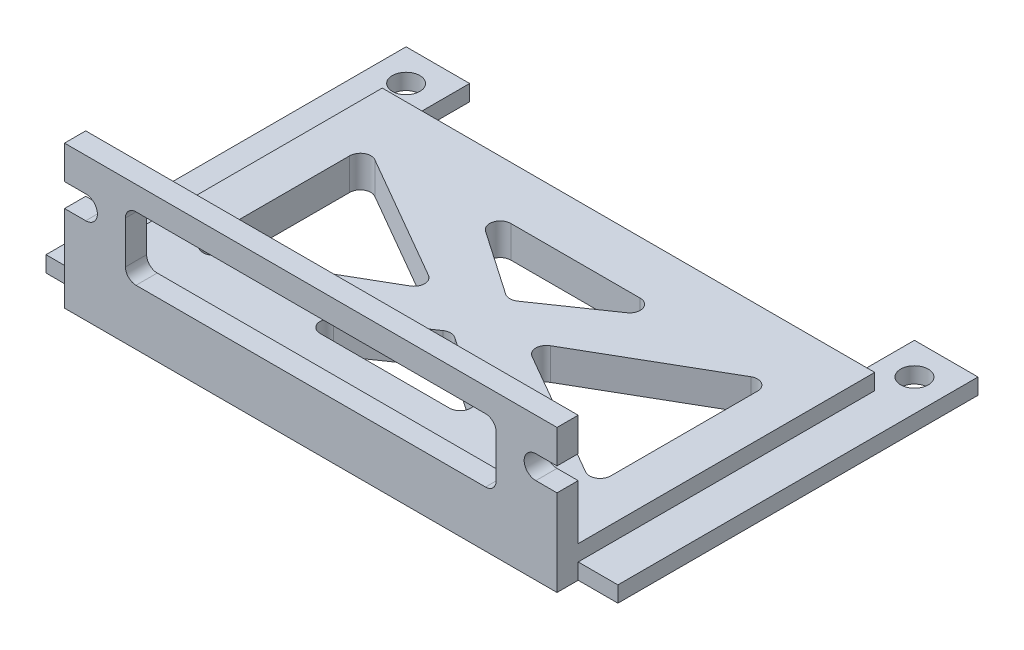
SolidWorks part; units mm, degrees
ref_plane "前视基准面" through (0, 0, 0) normal (0, 0, 1) x (1, 0, 0)
ref_plane "上视基准面" through (0, 0, 0) normal (0, 1, 0) x (1, 0, 0)
ref_plane "右视基准面" through (0, 0, 0) normal (1, 0, 0) x (0, 0, -1)
sketch "草图1" plane through (0, 0, 0) normal (0, 1, 0) x (1, 0, 0)
  line L1 (-46.5, -28) -> (46.5, -28) construction
  line L2 (-46.5, -28) -> (-46.5, 28) construction
  line L3 (-46.5, 28) -> (46.5, 28) construction
  line L4 (46.5, -28) -> (46.5, 28) construction
  line L5 (-46.5, -28) -> (46.5, 28) construction
  line L6 (-46.5, 28) -> (46.5, -28) construction
  line L7 (-58, -28) -> (58, -28)
  line L8 (-58, -28) -> (-58, 28)
  line L9 (-58, 28) -> (58, 28)
  line L10 (58, -28) -> (58, 28)
  line L11 (-58, -28) -> (58, 28) construction
  line L12 (-58, 28) -> (58, -28) construction
  point P0 (0, 0)
  point P6 (0, 0)
  dimension "D1" = 56
  dimension "D2" = 93
  dimension "D3" = 56
  dimension "D4" = 116
extrude "凸台-拉伸1" add sketch "草图1" along normal blind 3
sketch "草图2" plane through (0, 3, 0) normal (0, 1, 0) x (1, 0, 0)
  line L1 (-46.5, -28) -> (46.5, -28)
  line L2 (-46.5, -28) -> (-46.5, 28)
  line L3 (-46.5, 28) -> (46.5, 28)
  line L4 (46.5, -28) -> (46.5, 28)
  line L5 (-46.5, -28) -> (46.5, 28) construction
  line L6 (-46.5, 28) -> (46.5, -28) construction
  point P0 (0, 0)
extrude "凸台-拉伸2" add sketch "草图2" along normal blind 3
sketch "草图3" plane through (0, 0, 28) normal (0, 0, 1) x (1, 0, 0)
  line L0 (-46.5, 0) -> (-46.5, 27)
  line L1 (-58, 0) -> (58, 0) construction
  line L2 (-58, 0) -> (58, 0) construction
  line L3 (-46.5, 27) -> (46.5, 27)
  line L4 (46.5, 27) -> (46.5, 0)
  line L5 (-46.5, 0) -> (46.5, 0) construction
  line L6 (46.5, 0) -> (-46.5, 0)
  dimension "D1" = 27
  dimension "D2" = 93
extrude "凸台-拉伸3" add sketch "草图3" along normal blind 4
sketch "草图4" plane through (0, 3, 0) normal (0, 1, 0) x (1, 0, 0)
  line L0 (-46.5, 28) -> (-58, 28) construction
  line L1 (48, -34) -> (-48, -34) construction
  line L2 (48, -34) -> (48, 34) construction
  line L3 (48, 34) -> (-48, 34) construction
  line L4 (-48, -34) -> (-48, 34) construction
  line L5 (48, -34) -> (-48, 34) construction
  line L6 (48, 34) -> (-48, -34) construction
  point P0 (0, 0)
  point P6 (-48, 32.3311)
  dimension "D1" = 96
  dimension "D2" = 6
sketch "草图5" plane through (0, 3, 0) normal (0, 1, 0) x (1, 0, 0)
  line L5 (54, 40) -> (42, 40)
  line L6 (-54, 28) -> (-42, 28)
  line L7 (0, -12.7262) -> (0, 42.4626) construction
  line L12 (-54, 28) -> (-54, 40)
  line L13 (-54, 40) -> (-42, 40)
  line L14 (-42, 28) -> (-42, 40)
  line L15 (-54, 28) -> (-42, 40) construction
  line L16 (-54, 40) -> (-42, 28) construction
  line L17 (42, 28) -> (42, 40)
  line L18 (54, 28) -> (42, 28)
  line L19 (54, 28) -> (54, 40)
  point P0 (-48, 34)
  point P1 (-48, 34)
  dimension "D1" = 12
  dimension "D2" = 12
extrude "凸台-拉伸4" add sketch "草图5" against normal blind 3
sketch "草图6" plane through (0, 3, 0) normal (0, 1, 0) x (1, 0, 0)
  circle A0 centre (-48, 34) radius 2.6
  circle A1 centre (48, 34) radius 2.6
  dimension "D1" = 5.2
  dimension "D2" = 5.2
extrude "切除-拉伸1" cut sketch "草图6" against normal blind 3
sketch "草图7" plane through (0, 6, 0) normal (0, 1, 0) x (1, 0, 0)
  line L0 (-3.6525, 7.6752) -> (-32.1835, 27.3217) construction
  line L5 (48, 34) -> (-48, -34) construction
  line L6 (28.5, -18) -> (-28.5, -18) construction
  line L7 (-18.6463, 18) -> (0, 5.1602)
  line L8 (28.5, -18) -> (28.5, 18) construction
  line L9 (28.5, 18) -> (-28.5, 18) construction
  line L10 (-28.5, -18) -> (-28.5, 18) construction
  line L11 (28.5, -18) -> (-28.5, 18) construction
  line L12 (28.5, 18) -> (-28.5, -18) construction
  line L13 (-46.5, 28) -> (-46.5, -28) construction
  line L14 (46.5, 28) -> (-46.5, 28) construction
  line L15 (-4.426, 0) -> (4.9863, 0) construction
  line L16 (-8.5, 0) -> (-38.5, 17.3205)
  line L17 (-38.5, 17.3205) -> (-38.5, -17.3205)
  line L18 (-38.5, -17.3205) -> (-8.5, 0)
  line L19 (0, 6.0975) -> (0, -6.8288) construction
  line L20 (-18.6463, 18) -> (18.6463, 18)
  line L21 (18.6463, 18) -> (0, 5.1602)
  line L22 (38.5, -17.3205) -> (8.5, 0)
  line L23 (38.5, 17.3205) -> (38.5, -17.3205)
  line L24 (8.5, 0) -> (38.5, 17.3205)
  line L25 (-18.6463, -18) -> (18.6463, -18)
  line L26 (-18.6463, -18) -> (0, -5.1602)
  line L27 (18.6463, -18) -> (0, -5.1602)
  circle A0 centre (-28.5, 0) radius 10 construction
  point P0 (0, 0)
  point P27 (0, 18)
  dimension "D1" = 18
  dimension "D2" = 10
  dimension "D3" = 20
extrude "切除-拉伸2" cut sketch "草图7" against normal through all
sketch "草图8" plane through (0, 0, 28) normal (0, 0, -1) x (-1, 0, 0)
  line L0 (-46.5, 16.5) -> (0, 16.5) construction
  line L1 (-46.5, 6) -> (-46.5, 27) construction
  line L2 (0, 27) -> (0, 6) construction
  line L3 (-46.5, 27) -> (46.5, 27) construction
  line L4 (-46.5, 6) -> (46.5, 6) construction
  line L6 (-35, 10.5) -> (35, 10.5)
  line L7 (-35, 10.5) -> (-35, 22.5)
  line L8 (-35, 22.5) -> (35, 22.5)
  line L9 (35, 10.5) -> (35, 22.5)
  line L10 (-35, 10.5) -> (35, 22.5) construction
  line L11 (-35, 22.5) -> (35, 10.5) construction
  dimension "D1" = 70
  dimension "D2" = 12
extrude "切除-拉伸3" cut sketch "草图8" against normal through all
sketch "草图9" plane through (0, 0, -28) normal (0, 0, -1) x (-1, 0, 0)
  line L4 (54, 3) -> (54, 0)
  line L5 (54, 0) -> (58, 0)
  line L6 (58, 0) -> (58, 3)
  line L7 (58, 3) -> (54, 3)
  line L8 (54, 3) -> (54, 0)
  line L9 (54, 0) -> (58, 0)
  line L10 (58, 0) -> (58, 3)
  line L11 (58, 3) -> (54, 3)
  line L12 (-58, 0) -> (-54, 0)
  line L13 (-54, 0) -> (-54, 3)
  line L14 (-54, 3) -> (-58, 3)
  line L15 (-58, 3) -> (-58, 0)
  line L16 (-58, 0) -> (-54, 0)
  line L17 (-54, 0) -> (-54, 3)
  line L18 (-54, 3) -> (-58, 3)
  line L19 (-58, 3) -> (-58, 0)
  dimension "D1" = 0
  dimension "D2" = 0
extrude "切除-拉伸4" cut sketch "草图9" against normal through all
sketch "草图10" plane through (0, 0, 28) normal (0, 0, -1) x (-1, 0, 0)
  line L0 (-46.5, 18.5) -> (46.5, 18.5) construction
  line L1 (-46.5, 6) -> (-46.5, 27) construction
  line L2 (46.5, 27) -> (46.5, 6) construction
  line L3 (46.5, 6) -> (-46.5, 6) construction
  line L4 (-46.5, 18.5) -> (-42.5, 18.5) construction
  line L5 (-46.5, 20.7) -> (-42.5, 20.7)
  line L6 (-46.5, 16.3) -> (-42.5, 16.3)
  line L7 (0, 6) -> (0, 27) construction
  line L8 (-46.5, 27) -> (46.5, 27) construction
  line L9 (46.5, 18.5) -> (42.5, 18.5) construction
  line L10 (46.5, 20.7) -> (42.5, 20.7)
  line L11 (46.5, 16.3) -> (42.5, 16.3)
  arc A0 (-46.5, 20.7) -> (-46.5, 16.3) centre (-46.5, 18.5) ccw
  arc A1 (-42.5, 16.3) -> (-42.5, 20.7) centre (-42.5, 18.5) ccw
  arc A2 (46.5, 20.7) -> (46.5, 16.3) centre (46.5, 18.5) cw
  arc A3 (42.5, 16.3) -> (42.5, 20.7) centre (42.5, 18.5) cw
  point P8 (-44.5, 18.5)
  point P19 (44.5, 18.5)
  dimension "D3" = 2.2
  dimension "D1" = 12.5
  dimension "D2" = 4
extrude "切除-拉伸5" cut sketch "草图10" against normal through all
fillet "圆角1" radius 2 16 edges at (35, 22.5, 30) (-35, 22.5, 30) (-35, 10.5, 30) (35, 10.5, 30) (-38.5, 3, -17.3205) (-18.6463, 3, -18) (-38.5, 3, 17.3205) (0, 3, -5.1602) (18.6463, 3, -18) (-8.5, 3, 0) (-18.6463, 3, 18) (0, 3, 5.1602) (18.6463, 3, 18) (8.5, 3, 0) (38.5, 3, -17.3205) (38.5, 3, 17.3205)
